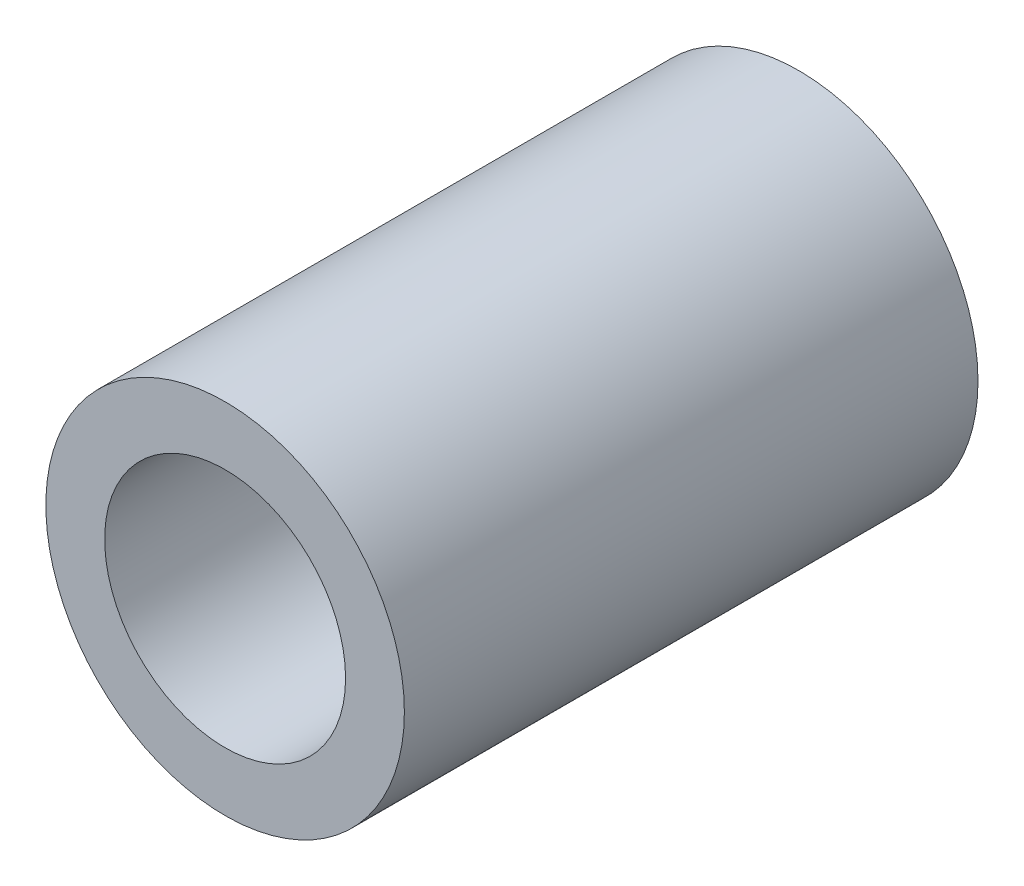
SolidWorks part; units mm, degrees
ref_plane "Front Plane" through (0, 0, 0) normal (0, 0, 1) x (1, 0, 0)
ref_plane "Top Plane" through (0, 0, 0) normal (0, 1, 0) x (1, 0, 0)
ref_plane "Right Plane" through (0, 0, 0) normal (1, 0, 0) x (0, 0, -1)
sketch "Sketch1" plane through (0, 0, 0) normal (1, 0, 0) x (0, 0, -1)
  line L0 (0, 1006.475) -> (210.82, 1006.475) construction
  line L1 (127, 1017.143) -> (101.6, 1017.143) construction
  line L6 (134.62, 1022.35) -> (185.42, 1022.35)
  line L7 (134.62, 1022.35) -> (134.62, 1017.143)
  line L8 (134.62, 1017.143) -> (185.42, 1017.143)
  line L9 (185.42, 1022.35) -> (185.42, 1017.143)
  line L10 (134.62, 1022.35) -> (210.82, 1022.35) construction
  line L11 (210.82, 1022.35) -> (210.82, 990.6) construction
  point P20 (185.42, 1019.7465)
  dimension "D1" = 25.4
revolve "Revolve1" add sketch "Sketch1" angle 360 about L0
